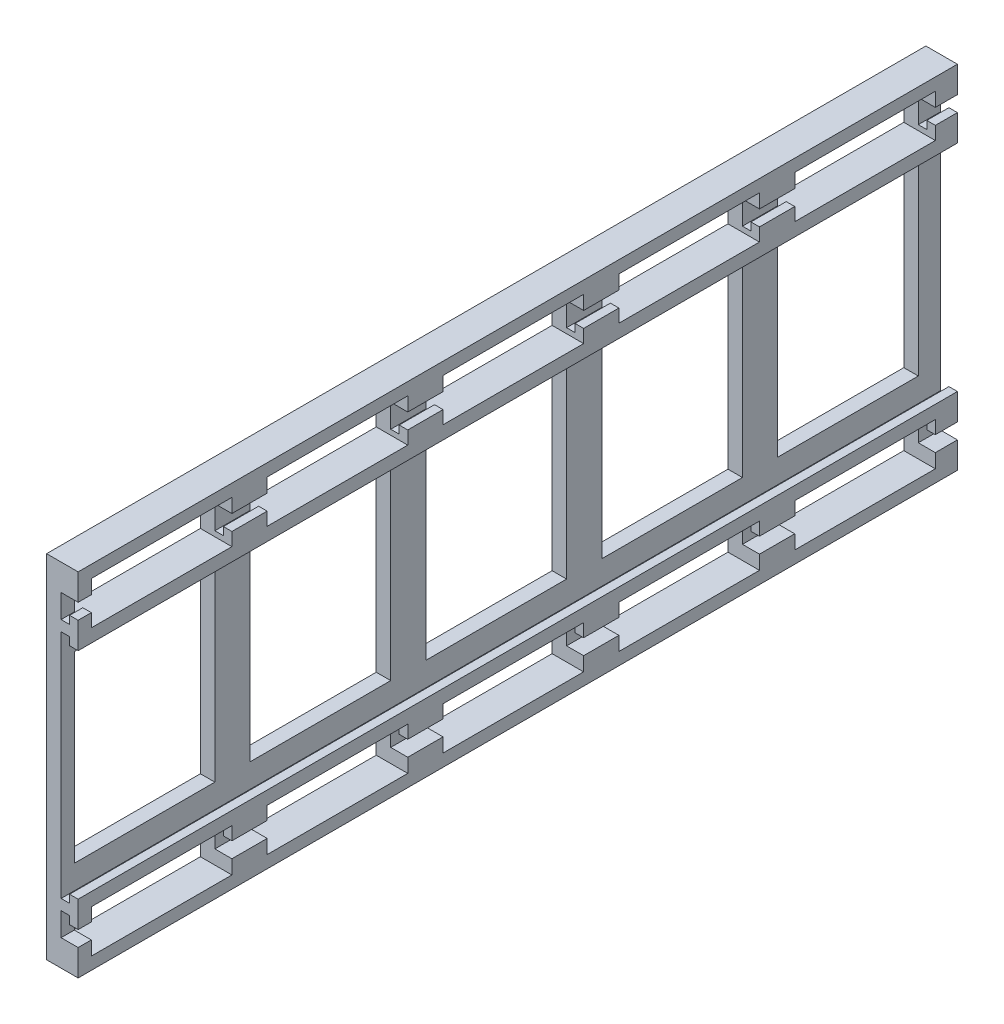
SolidWorks part; units mm, degrees
ref_plane "Front Plane" through (0, 0, 0) normal (0, 0, 1) x (1, 0, 0)
ref_plane "Top Plane" through (0, 0, 0) normal (0, 1, 0) x (1, 0, 0)
ref_plane "Right Plane" through (0, 0, 0) normal (1, 0, 0) x (0, 0, -1)
sketch "Sketch1" plane through (0, 0, 0) normal (0, 0, 1) x (0, 1, 0)
  line L0 (-379.2608, -1250.0917) -> (-356.4008, -1250.0917)
  line L1 (-553.642, -1183.5954) -> (462.358, -1183.5954)
  line L2 (-553.642, -1183.5954) -> (-553.642, -1274.7002)
  line L3 (-553.642, -1274.7002) -> (-477.442, -1274.7002)
  line L4 (287.9768, -1225.4832) -> (265.1168, -1225.4832)
  line L5 (-356.4008, -1274.7002) -> (-356.4008, -1250.0917)
  line L6 (-432.6008, -1274.7002) -> (-432.6008, -1250.0917)
  line L8 (-432.6008, -1225.4832) -> (-477.442, -1225.4832)
  line L9 (-477.442, -1225.4832) -> (-477.442, -1274.7002)
  line L10 (-432.6008, -1274.7002) -> (-356.4008, -1274.7002)
  line L11 (-477.442, -1183.5954) -> (-477.442, -1274.7002) construction
  line L12 (-356.4008, -1225.4832) -> (265.1168, -1225.4832)
  line L13 (318.4568, -1225.4832) -> (341.3168, -1225.4832)
  line L14 (-432.6008, -1250.0917) -> (-409.7408, -1250.0917)
  line L15 (-379.2608, -1250.0917) -> (-379.2608, -1225.4832)
  line L16 (-409.7408, -1250.0917) -> (-409.7408, -1225.4832)
  line L17 (-409.7408, -1225.4832) -> (-432.6008, -1225.4832)
  line L18 (-379.2608, -1225.4832) -> (-356.4008, -1225.4832)
  line L19 (318.4568, -1250.0917) -> (318.4568, -1225.4832)
  line L20 (287.9768, -1250.0917) -> (287.9768, -1225.4832)
  line L21 (341.3168, -1250.0917) -> (318.4568, -1250.0917)
  line L22 (341.3168, -1274.7002) -> (265.1168, -1274.7002)
  line L23 (386.158, -1225.4832) -> (386.158, -1274.7002)
  line L24 (341.3168, -1225.4832) -> (386.158, -1225.4832)
  line L25 (341.3168, -1274.7002) -> (341.3168, -1250.0917)
  line L26 (265.1168, -1274.7002) -> (265.1168, -1250.0917)
  line L27 (462.358, -1274.7002) -> (386.158, -1274.7002)
  line L28 (462.358, -1183.5954) -> (462.358, -1274.7002)
  line L29 (287.9768, -1250.0917) -> (265.1168, -1250.0917)
  point P28 (-45.642, -1225.4832)
  point P33 (-45.642, -1183.5954)
  dimension "D4" = 76.2
extrude "Extrude1" add sketch "Sketch1" along normal blind 2540
sketch "Sketch2" plane through (1225.4832, 0, 0) normal (1, 0, 0) x (0, 0, -1)
  line L0 (-1587.7743, -517.9428) -> (-1587.7743, -394.6031)
  line L3 (-2095.7743, -517.9428) -> (-2095.7743, -394.6031)
  line L4 (-2501.8928, 219.0871) -> (-2095.7743, 219.0871)
  line L5 (-2501.8928, 219.0871) -> (-2501.8928, -310.3711)
  line L6 (-2501.8928, -394.6031) -> (-2095.7743, -394.6031)
  line L7 (-2095.7743, 219.0871) -> (-2095.7743, -310.3711)
  line L8 (-2501.8928, 426.6588) -> (-2095.7743, 426.6588)
  line L9 (-2501.8928, 426.6588) -> (-2501.8928, 303.3191)
  line L10 (-2501.8928, 303.3191) -> (-2095.7743, 303.3191)
  line L11 (-2095.7743, 426.6588) -> (-2095.7743, 303.3191)
  line L12 (-2501.8928, -517.9428) -> (-2501.8928, -394.6031)
  line L13 (-2501.8928, -517.9428) -> (-2095.7743, -517.9428)
  line L14 (-2501.8928, -310.3711) -> (-2095.7743, -310.3711)
  line L15 (-1993.8928, 219.0871) -> (-1587.7743, 219.0871)
  line L16 (-1993.8928, 219.0871) -> (-1993.8928, -310.3711)
  line L17 (-1993.8928, -394.6031) -> (-1587.7743, -394.6031)
  line L18 (-1587.7743, 219.0871) -> (-1587.7743, -310.3711)
  line L19 (-1993.8928, 426.6588) -> (-1587.7743, 426.6588)
  line L20 (-1993.8928, 426.6588) -> (-1993.8928, 303.3191)
  line L21 (-1993.8928, 303.3191) -> (-1587.7743, 303.3191)
  line L22 (-1587.7743, 426.6588) -> (-1587.7743, 303.3191)
  line L23 (-1993.8928, -517.9428) -> (-1993.8928, -394.6031)
  line L24 (-1993.8928, -517.9428) -> (-1587.7743, -517.9428)
  line L25 (-1993.8928, -310.3711) -> (-1587.7743, -310.3711)
  line L26 (-1079.7743, -517.9428) -> (-1079.7743, -394.6031)
  line L27 (-1485.8928, 219.0871) -> (-1079.7743, 219.0871)
  line L28 (-1485.8928, 219.0871) -> (-1485.8928, -310.3711)
  line L29 (-1485.8928, -394.6031) -> (-1079.7743, -394.6031)
  line L30 (-1079.7743, 219.0871) -> (-1079.7743, -310.3711)
  line L31 (-1485.8928, 426.6588) -> (-1079.7743, 426.6588)
  line L32 (-1485.8928, 426.6588) -> (-1485.8928, 303.3191)
  line L33 (-1485.8928, 303.3191) -> (-1079.7743, 303.3191)
  line L34 (-1079.7743, 426.6588) -> (-1079.7743, 303.3191)
  line L35 (-1485.8928, -517.9428) -> (-1485.8928, -394.6031)
  line L36 (-1485.8928, -517.9428) -> (-1079.7743, -517.9428)
  line L37 (-1485.8928, -310.3711) -> (-1079.7743, -310.3711)
  line L38 (-571.7743, -517.9428) -> (-571.7743, -394.6031)
  line L39 (-977.8928, 219.0871) -> (-571.7743, 219.0871)
  line L40 (-977.8928, 219.0871) -> (-977.8928, -310.3711)
  line L41 (-977.8928, -394.6031) -> (-571.7743, -394.6031)
  line L42 (-571.7743, 219.0871) -> (-571.7743, -310.3711)
  line L43 (-977.8928, 426.6588) -> (-571.7743, 426.6588)
  line L44 (-977.8928, 426.6588) -> (-977.8928, 303.3191)
  line L45 (-977.8928, 303.3191) -> (-571.7743, 303.3191)
  line L46 (-571.7743, 426.6588) -> (-571.7743, 303.3191)
  line L47 (-977.8928, -517.9428) -> (-977.8928, -394.6031)
  line L48 (-977.8928, -517.9428) -> (-571.7743, -517.9428)
  line L49 (-977.8928, -310.3711) -> (-571.7743, -310.3711)
  line L50 (-63.7743, -517.9428) -> (-63.7743, -394.6031)
  line L51 (-469.8928, 219.0871) -> (-63.7743, 219.0871)
  line L52 (-469.8928, 219.0871) -> (-469.8928, -310.3711)
  line L53 (-469.8928, -394.6031) -> (-63.7743, -394.6031)
  line L54 (-63.7743, 219.0871) -> (-63.7743, -310.3711)
  line L55 (-469.8928, 426.6588) -> (-63.7743, 426.6588)
  line L56 (-469.8928, 426.6588) -> (-469.8928, 303.3191)
  line L57 (-469.8928, 303.3191) -> (-63.7743, 303.3191)
  line L58 (-63.7743, 426.6588) -> (-63.7743, 303.3191)
  line L59 (-469.8928, -517.9428) -> (-469.8928, -394.6031)
  line L60 (-469.8928, -517.9428) -> (-63.7743, -517.9428)
  line L61 (-469.8928, -310.3711) -> (-63.7743, -310.3711)
  point P19 (-2095.7743, -45.642)
  point P20 (-2501.8928, -45.642)
  point P27 (-1587.7743, -45.642)
  point P28 (-1993.8928, -45.642)
  point P41 (-1079.7743, -45.642)
  point P42 (-1485.8928, -45.642)
  point P55 (-571.7743, -45.642)
  point P56 (-977.8928, -45.642)
  point P69 (-63.7743, -45.642)
  point P70 (-469.8928, -45.642)
extrude "Extrude2" cut sketch "Sketch2" against normal through all from offset 88.9
